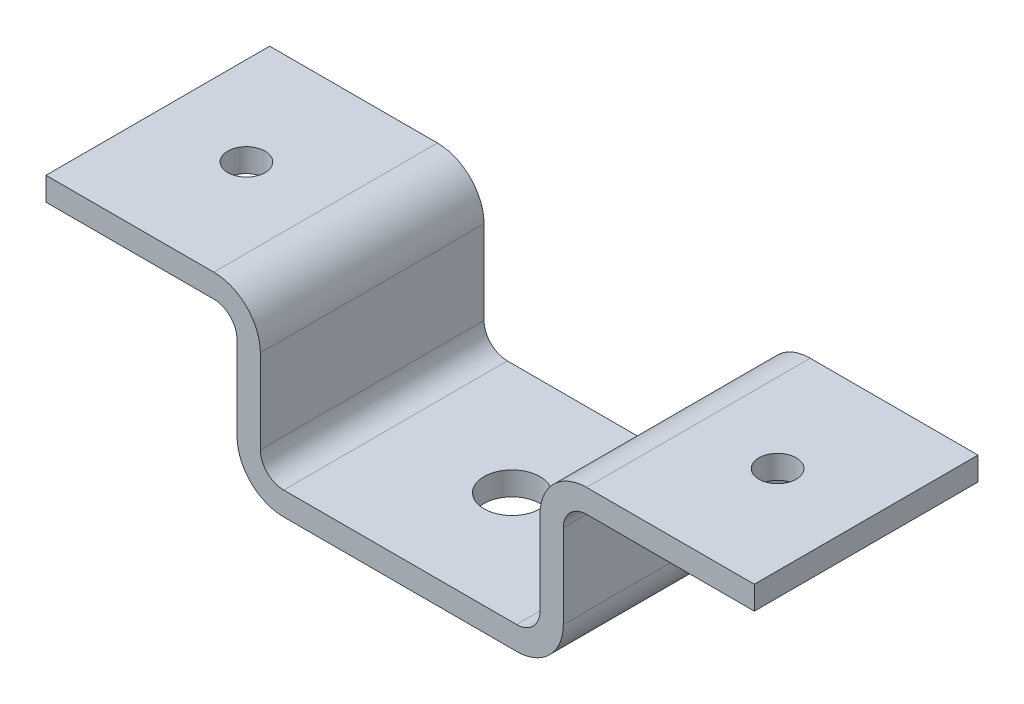
SolidWorks part; units mm, degrees
material "201 Annealed Stainless Steel (SS)"
ref_plane "Front Plane" through (0, 0, 0) normal (0, 0, 1) x (1, 0, 0)
ref_plane "Top Plane" through (0, 0, 0) normal (0, 1, 0) x (1, 0, 0)
ref_plane "Right Plane" through (0, 0, 0) normal (1, 0, 0) x (0, 0, -1)
sketch "Sketch1" plane through (0, 0, 0) normal (0, 1, 0) x (1, 0, 0)
  line L0 (0, 0) -> (0, 76.2)
  line L1 (0, 76.2) -> (241.3, 76.2)
  line L2 (241.3, 76.2) -> (241.3, 0)
  line L3 (241.3, 0) -> (0, 0)
  dimension "D1" = 76.2
  dimension "D2" = 241.3
extrude "Boss-Extrude1" add sketch "Sketch1" along normal blind 60.325
sketch "Sketch3" plane through (0, 0, 0) normal (0, 0, 1) x (1, 0, 0)
  line L1 (241.3, 60.325) -> (241.3, 0) construction
  line L6 (241.3, 0) -> (241.3, 52.3748)
  line L9 (176.2252, 52.3748) -> (176.2252, 0)
  line L10 (176.2252, 52.3748) -> (241.3, 52.3748)
  line L11 (176.2252, 0) -> (241.3, 0)
  dimension "D1" = 65.0748
  dimension "D2" = 52.3748
extrude "Cut-Extrude4" cut sketch "Sketch3" against normal through all
sketch "Sketch6" plane through (0, 0, 0) normal (0, 0, 1) x (1, 0, 0)
  line L0 (176.2252, 52.3748) -> (176.2252, 0) construction
  line L4 (168.275, 7.9502) -> (168.275, 60.325)
  line L5 (0, 60.325) -> (241.3, 60.325) construction
  line L10 (73.025, 60.325) -> (168.275, 60.325)
  line L11 (73.025, 60.325) -> (73.025, 7.9502)
  line L12 (73.025, 7.9502) -> (168.275, 7.9502)
  dimension "D1" = 52.3748
  dimension "D2" = 95.25
  dimension "D3" = 7.9502
extrude "Cut-Extrude5" cut sketch "Sketch6" against normal through all
sketch "Sketch7" plane through (0, 0, 0) normal (0, 0, 1) x (1, 0, 0)
  line L5 (65.0748, 52.3748) -> (65.0748, 0)
  line L6 (0, 0) -> (176.2252, 0) construction
  line L7 (65.0748, 0) -> (0, 0)
  line L8 (0, 0) -> (0, 52.3748)
  line L9 (0, 60.325) -> (0, 0) construction
  line L10 (0, 52.3748) -> (65.0748, 52.3748)
  dimension "D1" = 65.0748
  dimension "D2" = 52.3748
extrude "Cut-Extrude6" cut sketch "Sketch7" against normal through all
sketch "Sketch8" plane through (0, 60.325, 0) normal (0, 1, 0) x (1, 0, 0)
  line L0 (73.025, 76.2) -> (0, 76.2) construction
  line L3 (0, 76.2) -> (0, 0) construction
  line L4 (241.3, 76.2) -> (168.275, 76.2) construction
  line L6 (241.3, 0) -> (241.3, 76.2) construction
  circle A0 centre (30.1752, 38.1) radius 6.35
  circle A1 centre (211.1248, 38.1) radius 6.35
  dimension "D3" = 12.7
  dimension "D2" = 30.1752
  dimension "D6" = 12.7
  dimension "D1" = 38.1
  dimension "D4" = 38.1
  dimension "D5" = 30.1752
extrude "Cut-Extrude7" cut sketch "Sketch8" against normal through all
sketch "Sketch9" plane through (0, 60.325, 0) normal (0, 1, 0) x (1, 0, 0)
  line L0 (73.025, 76.2) -> (168.275, 76.2) construction
  line L2 (168.275, 76.2) -> (168.275, 0) construction
  circle A0 centre (120.65, 38.1) radius 9.525
  dimension "D2" = 19.05
  dimension "D1" = 38.1
  dimension "D3" = 47.625
extrude "Cut-Extrude8" cut sketch "Sketch9" against normal through all
fillet "Fillet1" radius 15.875 1 edges at (73.025, 60.325, -38.1)
fillet "Fillet2" radius 7.9502 1 edges at (73.025, 7.9502, -38.1)
fillet "Fillet3" radius 7.9502 1 edges at (168.275, 7.9502, -38.1)
fillet "Fillet4" radius 15.875 1 edges at (168.275, 60.325, -38.1)
fillet "Fillet5" radius 15.875 1 edges at (176.2252, 0, -38.1)
fillet "Fillet6" radius 15.875 1 edges at (65.0748, 0, -38.1)
fillet "Fillet7" radius 7.9502 1 edges at (65.0748, 52.3748, -38.1)
fillet "Fillet8" radius 7.9502 1 edges at (176.2252, 52.3748, -38.1)
